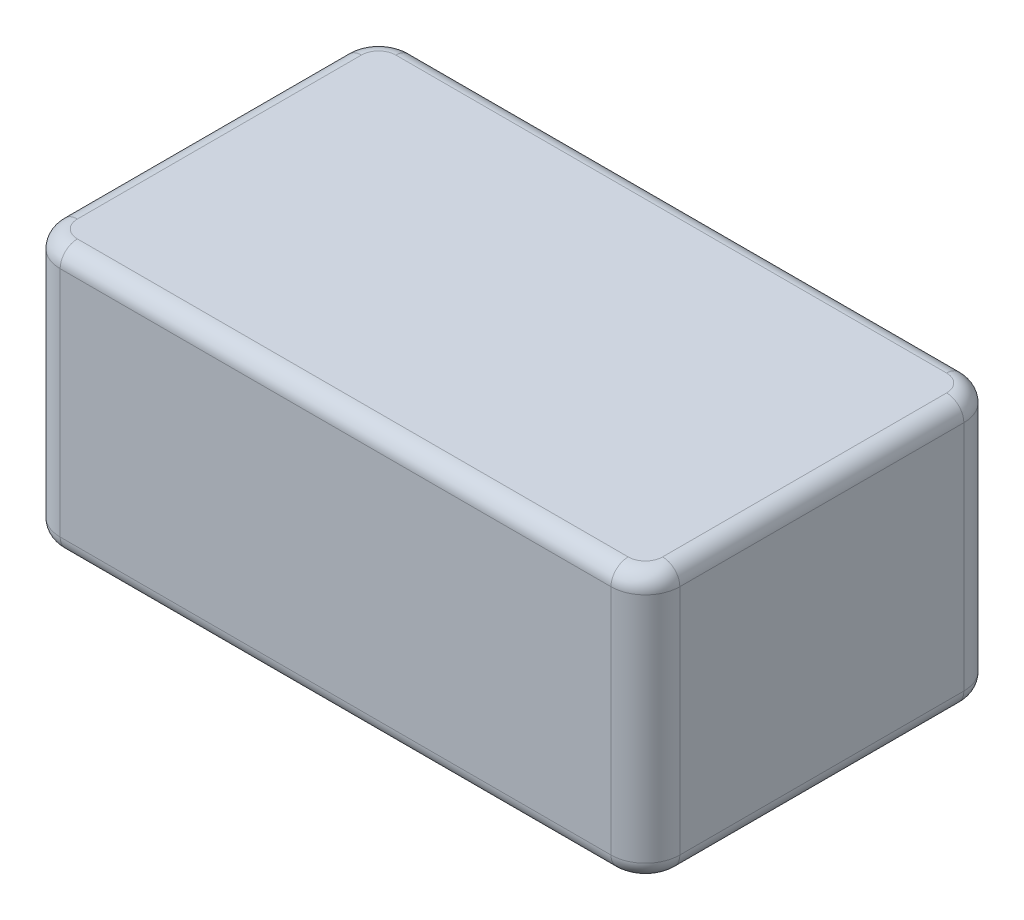
SolidWorks part; units mm, degrees
ref_plane "Front Plane" through (0, 0, 0) normal (0, 0, 1) x (1, 0, 0)
ref_plane "Top Plane" through (0, 0, 0) normal (0, 1, 0) x (1, 0, 0)
ref_plane "Right Plane" through (0, 0, 0) normal (1, 0, 0) x (0, 0, -1)
sketch "Sketch1" plane through (0, 0, 0) normal (0, 1, 0) x (1, 0, 0)
  line L1 (0, 0) -> (36, 0)
  line L2 (0, 0) -> (0, 20.5)
  line L3 (0, 20.5) -> (36, 20.5)
  line L4 (36, 0) -> (36, 20.5)
  dimension "D1" = 36
  dimension "D2" = 20.5
extrude "Boss-Extrude1" add sketch "Sketch1" along normal blind 15.5
fillet "Fillet1" radius 2 4 edges at (0, 7.75, -20.5) (36, 7.75, -20.5) (36, 7.75, 0) (0, 7.75, 0)
fillet "Fillet2" radius 1 16 edges at (0.5858, 0, -0.5858) (0, 0, -10.25) (0.5858, 0, -19.9142) (18, 0, -20.5) (35.4142, 0, -19.9142) (36, 0, -10.25) (35.4142, 0, -0.5858) (0.5858, 15.5, -0.5858) (0, 15.5, -10.25) (0.5858, 15.5, -19.9142) (18, 15.5, -20.5) (35.4142, 15.5, -19.9142) (36, 15.5, -10.25) (35.4142, 15.5, -0.5858) (18, 0, 0) (18, 15.5, 0)
